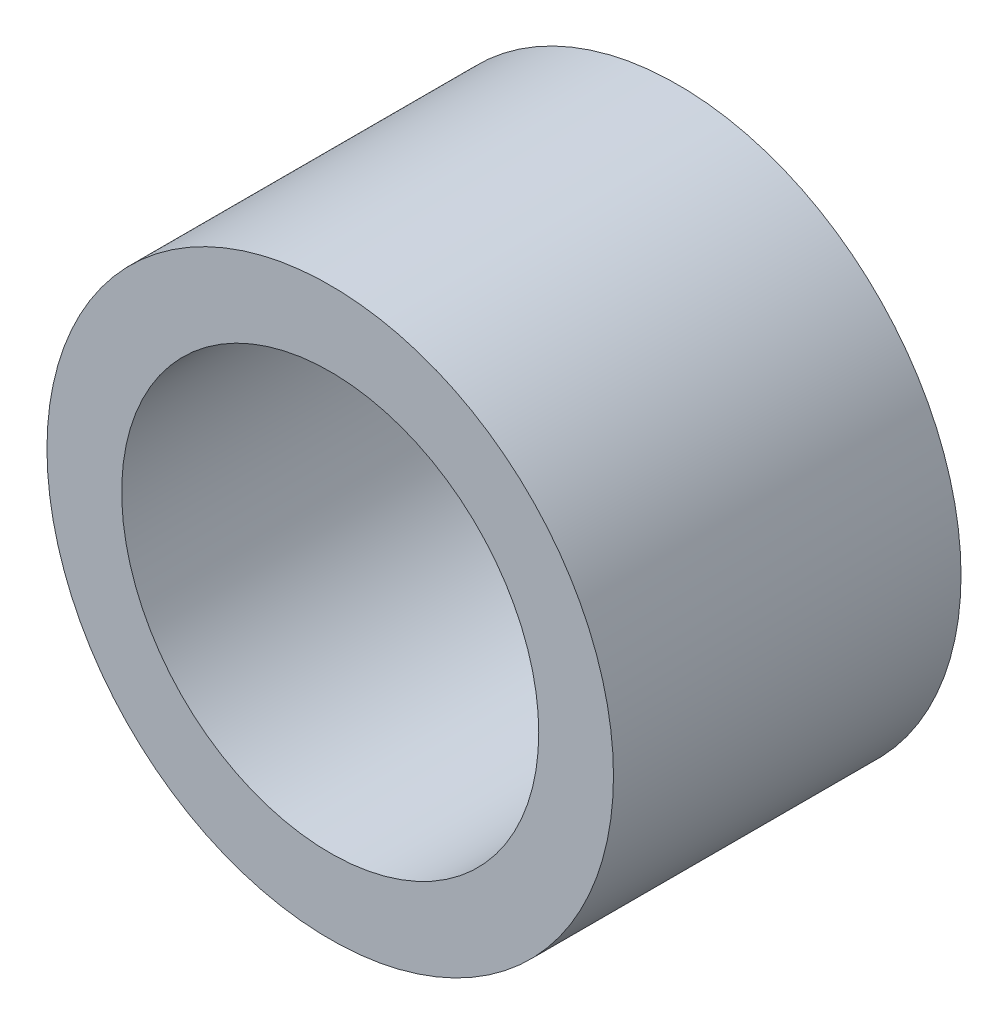
SolidWorks part; units mm, degrees
ref_plane "Ön Düzlem" through (0, 0, 0) normal (0, 0, 1) x (1, 0, 0)
ref_plane "Üst Düzlem" through (0, 0, 0) normal (0, 1, 0) x (1, 0, 0)
ref_plane "Sağ Düzlem" through (0, 0, 0) normal (1, 0, 0) x (0, 0, -1)
sketch "Sketch1" plane through (0, 0, 0) normal (0, 0, 1) x (1, 0, 0)
  circle A0 centre (0, 0) radius 3
  circle A1 centre (0, 0) radius 4.075
  dimension "D1" = 6
  dimension "D2" = 8.15
extrude "Boss-Extrude1" add sketch "Sketch1" along normal blind 5
